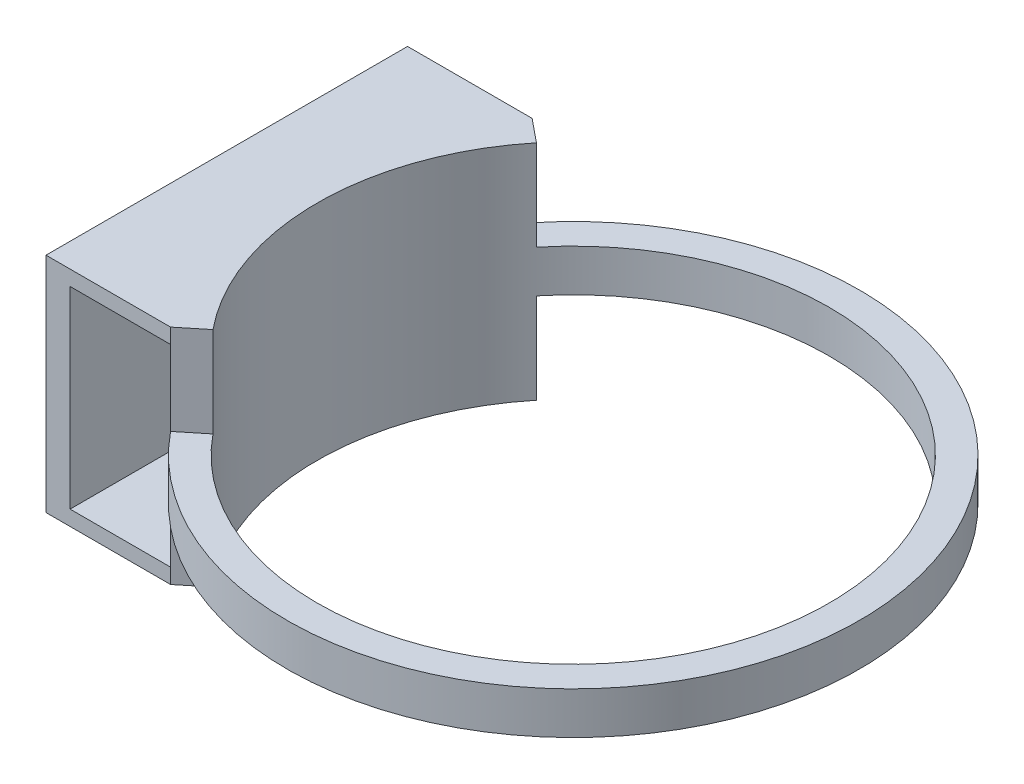
SolidWorks part; units mm, degrees
ref_plane "前视基准面" through (0, 0, 0) normal (0, 0, 1) x (1, 0, 0)
ref_plane "上视基准面" through (0, 0, 0) normal (0, 1, 0) x (1, 0, 0)
ref_plane "右视基准面" through (0, 0, 0) normal (1, 0, 0) x (0, 0, -1)
sketch "草图1" plane through (0, 0, 0) normal (0, 1, 0) x (1, 0, 0)
  line L0 (0, 0) -> (-11.5, 0) construction
  line L1 (-11.5, 0) -> (-11.5, 6) construction
  line L2 (-11.5, 0) -> (-11.5, -6) construction
  line L5 (-11.5, 6) -> (-11.5, -6)
  line L6 (-11.5, 6) -> (-7.3655, 6)
  line L7 (-11.5, -6) -> (-7.3655, -6)
  circle A0 centre (0, 0) radius 8.5
  arc A3 (-7.3655, -6) -> (-7.3655, 6) centre (0, 0) ccw
extrude "凸台-拉伸1" add sketch "草图1" along normal blind 0.5
sketch "草图5" plane through (0, 0.5, 0) normal (0, 1, 0) x (1, 0, 0)
  line L1 (-11.5, 6) -> (-10.7, 6)
  line L2 (-11.5, 6) -> (-11.5, -6)
  line L3 (-11.5, -6) -> (-10.7, -6)
  line L4 (-10.7, 6) -> (-10.7, -6)
  circle A0 centre (0, 0) radius 8.5
  circle A1 centre (0, 0) radius 9.5
extrude "凸台-拉伸4" add sketch "草图5" along normal blind 6.4
sketch "草图6" plane through (0, 6.9, 0) normal (0, 1, 0) x (1, 0, 0)
  line L0 (-11.5, 6) -> (-11.5, -6)
  line L1 (-11.5, 6) -> (-7.3655, 6)
  line L2 (-11.5, -6) -> (-7.3655, -6)
  circle A0 centre (0, 0) radius 8.5
  arc A1 (-7.3655, -6) -> (-7.3655, 6) centre (0, 0) ccw
extrude "凸台-拉伸5" add sketch "草图6" along normal blind 0.5
sketch "草图7" plane through (0, 7.4, 0) normal (0, 1, 0) x (1, 0, 0)
  line L0 (-7.3655, 6) -> (-6.5901, 5.3684)
  line L1 (-7.3655, -6) -> (-6.5901, -5.3684)
  arc A0 (-7.3655, -6) -> (-7.3655, 6) centre (0, 0) ccw
  arc A1 (-6.5901, -5.3684) -> (-6.5901, 5.3684) centre (0, 0) ccw
extrude "切除-拉伸1" cut sketch "草图7" against normal blind 3
sketch "草图8" plane through (0, 0, 0) normal (0, -1, 0) x (-1, 0, 0)
  line L0 (7.3655, -6) -> (6.5901, -5.3684)
  line L1 (7.3655, 6) -> (6.5901, 5.3684)
  arc A0 (6.5901, 5.3684) -> (6.5901, -5.3684) centre (0, 0) ccw
  arc A1 (7.3655, 6) -> (7.3655, -6) centre (0, 0) ccw
extrude "切除-拉伸2" cut sketch "草图8" against normal blind 3
